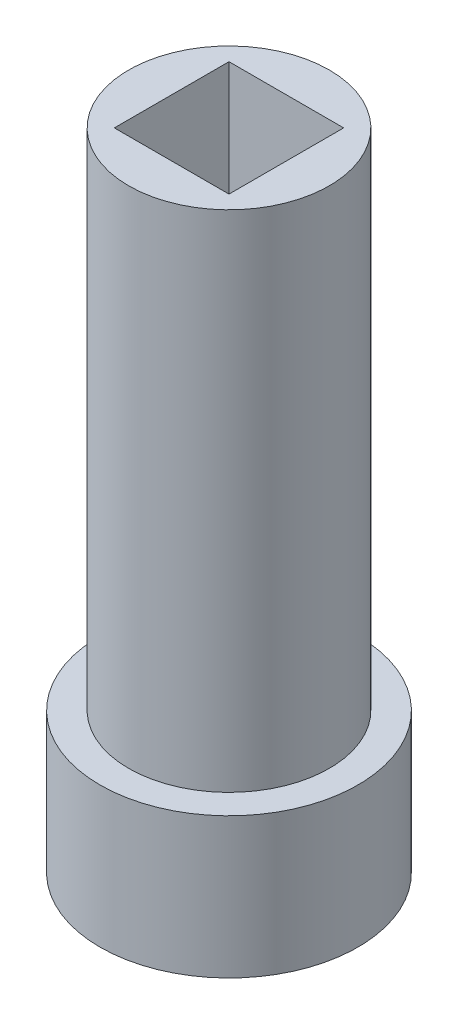
SolidWorks part; units mm, degrees
ref_plane "Front Plane" through (0, 0, 0) normal (0, 0, 1) x (1, 0, 0)
ref_plane "Top Plane" through (0, 0, 0) normal (0, 1, 0) x (1, 0, 0)
ref_plane "Right Plane" through (0, 0, 0) normal (1, 0, 0) x (0, 0, -1)
sketch "Sketch1" plane through (0, 0, 0) normal (0, 1, 0) x (1, 0, 0)
  circle A0 centre (0, 0) radius 7
  dimension "D1" = 14
extrude "Boss-Extrude1" add sketch "Sketch1" along normal blind 45
sketch "Sketch2" plane through (0, 45, 0) normal (0, 1, 0) x (1, 0, 0)
  line L1 (-4, 4) -> (4, 4)
  line L2 (-4, 4) -> (-4, -4)
  line L3 (-4, -4) -> (4, -4)
  line L4 (4, 4) -> (4, -4)
  circle A0 centre (0, 0) radius 7 construction
  dimension "D3" = 4
  dimension "D1" = 4
  dimension "D2" = 4
  dimension "D4" = 4
extrude "Cut-Extrude1" cut sketch "Sketch2" against normal blind 22
sketch "Sketch3" plane through (0, 0, 0) normal (0, -1, 0) x (1, 0, 0)
  circle A0 centre (0, 0) radius 9
  dimension "D1" = 18
extrude "Boss-Extrude2" add sketch "Sketch3" against normal blind 9.8
